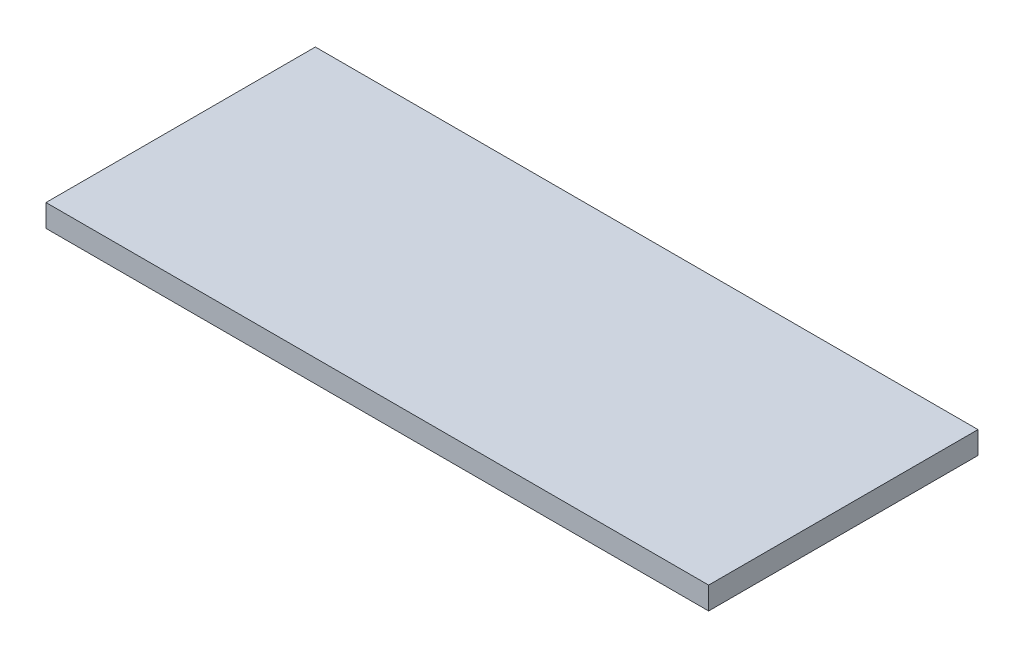
SolidWorks part; units mm, degrees
ref_plane "Front Plane" through (0, 0, 0) normal (0, 0, 1) x (1, 0, 0)
ref_plane "Top Plane" through (0, 0, 0) normal (0, 1, 0) x (1, 0, 0)
ref_plane "Right Plane" through (0, 0, 0) normal (1, 0, 0) x (0, 0, -1)
sketch "Sketch1" plane through (0, 0, 0) normal (0, 1, 0) x (1, 0, 0)
  line L1 (-93.726, 38.1) -> (93.726, 38.1)
  line L2 (-93.726, 38.1) -> (-93.726, -38.1)
  line L3 (-93.726, -38.1) -> (93.726, -38.1)
  line L4 (93.726, 38.1) -> (93.726, -38.1)
  line L5 (-93.726, 38.1) -> (93.726, -38.1) construction
  line L6 (-93.726, -38.1) -> (93.726, 38.1) construction
  point P0 (0, 0)
  dimension "D1" = 76.2
  dimension "D2" = 187.452
extrude "Boss-Extrude1" add sketch "Sketch1" along normal blind 6.35
